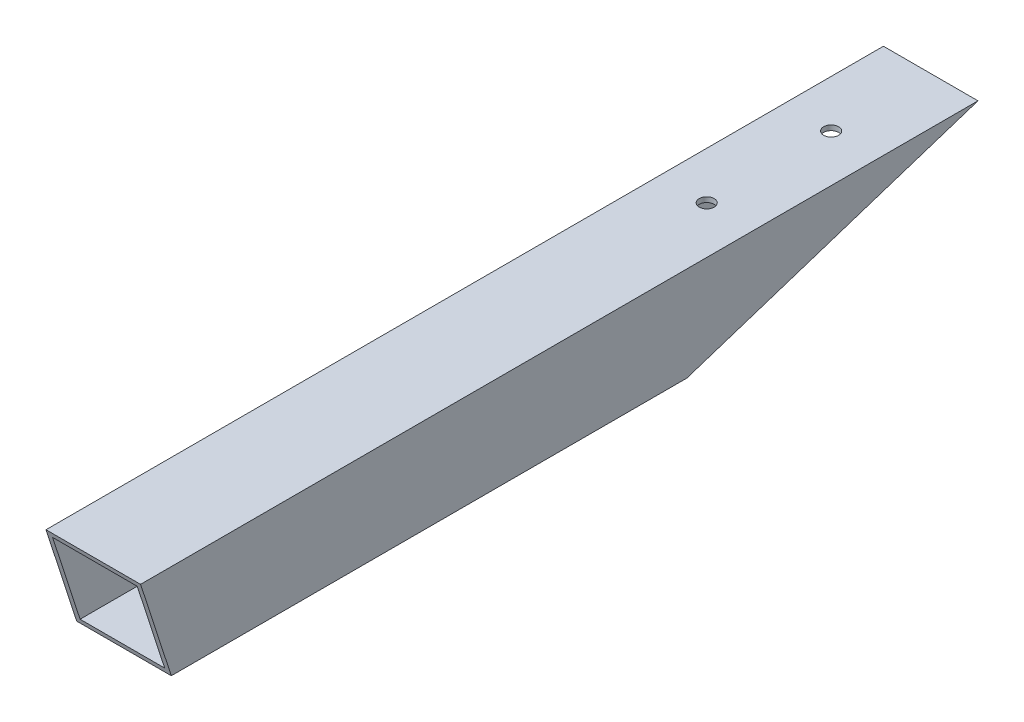
SolidWorks part; units mm, degrees
material "Gerais  - 6061-T6"
ref_plane "Plano frontal" through (0, 0, 0) normal (0, 0, 1) x (1, 0, 0)
ref_plane "Plano superior" through (0, 0, 0) normal (0, 1, 0) x (1, 0, 0)
ref_plane "Plano direito" through (0, 0, 0) normal (1, 0, 0) x (0, 0, -1)
sketch "Esboço1" plane through (0, 0, 0) normal (0, 0, 1) x (1, 0, 0)
  line L1 (-9.5, 9.5) -> (9.5, 9.5)
  line L2 (-9.5, 9.5) -> (-9.5, -9.5)
  line L3 (-9.5, -9.5) -> (9.5, -9.5)
  line L4 (9.5, 9.5) -> (9.5, -9.5)
  line L5 (-9.5, 9.5) -> (9.5, -9.5) construction
  line L6 (-9.5, -9.5) -> (9.5, 9.5) construction
  line L11 (-5.6574, 5.6574) -> (5.6574, -5.6574) construction
  line L12 (-5.6574, -5.6574) -> (5.6574, 5.6574) construction
  point P0 (0, 0)
  point P6 (0, 0)
  dimension "D1" = 19
extrude "Ressalto-extrusão1" add sketch "Esboço1" along normal blind 260
shell "Casca2" thickness 1
sketch "Esboço2" plane through (9.5, 0, 0) normal (1, 0, 0) x (0, 0, -1)
  line L0 (0, 9.5) -> (-58.476, -9.5)
  line L1 (-260, -9.5) -> (0, -9.5) construction
  line L4 (-260, 9.5) -> (0, 9.5) construction
  line L5 (-58.476, -9.5) -> (0, -9.5)
  line L7 (0, -9.5) -> (0, 9.5)
  dimension "D1" = 18
extrude "Corte-extrusão1" cut sketch "Esboço2" against normal through all
sketch "Esboço4" plane through (9.5, 0, 0) normal (1, 0, 0) x (0, 0, -1)
  line L0 (-168.5503, 10.4737) -> (-161.2895, -11.8728)
  line L1 (-161.2895, -11.8728) -> (-264.8128, -45.5096)
  line L2 (-264.8128, -45.5096) -> (-289.0578, 22.1497)
  line L3 (-289.0578, 22.1497) -> (-184.5161, 59.6112)
  line L4 (-184.5161, 59.6112) -> (-168.5503, 10.4737)
extrude "Corte-extrusão3" cut sketch "Esboço4" against normal through all
sketch "Esboço5" plane through (0, 9.5, 0) normal (0, 1, 0) x (1, 0, 0)
  circle A0 centre (0, -20) radius 1.5
  circle A1 centre (0, -45) radius 1.5
  dimension "D3" = 3
  dimension "D1" = 20
  dimension "D2" = 25
extrude "Corte-extrusão4" cut sketch "Esboço5" against normal through all
